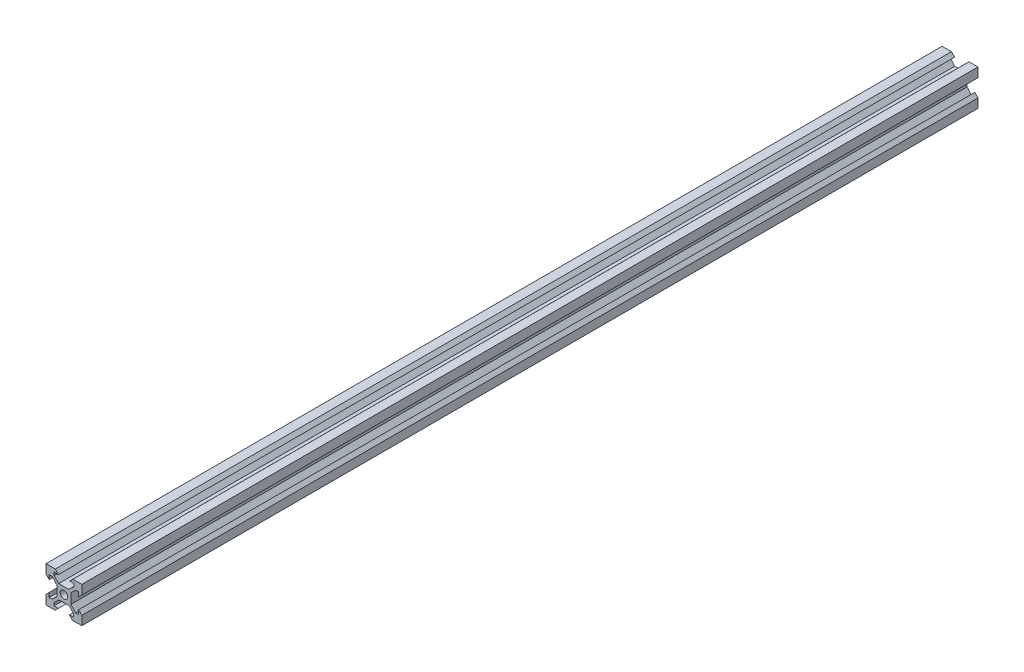
SolidWorks part; units mm, degrees
material "1060-H12"
ref_plane "Płaszczyzna przednia" through (0, 0, 0) normal (0, 0, 1) x (1, 0, 0)
ref_plane "Płaszczyzna górna" through (0, 0, 0) normal (0, 1, 0) x (1, 0, 0)
ref_plane "Płaszczyzna prawa" through (0, 0, 0) normal (1, 0, 0) x (0, 0, -1)
sketch "Szkic1" plane through (0, 0, 0) normal (0, 0, 1) x (1, 0, 0)
  line L0 (7.0398, 13.8855) -> (12.7198, 13.8855)
  line L1 (0, 0) -> (5, 0)
  line L2 (0, 0) -> (0, 5.1987)
  line L3 (0, 20) -> (5.1987, 20)
  line L4 (20, 0) -> (20, 5)
  line L6 (6.9691, 18.1996) -> (5.1987, 20)
  line L7 (13.1691, 18.1996) -> (15, 20)
  line L9 (15, 20) -> (20, 20)
  line L10 (4.5691, 18.1996) -> (6.9691, 18.1996)
  line L11 (4.5691, 18.1996) -> (4.5691, 16.5388)
  line L12 (15.5691, 18.1996) -> (15.5691, 16.5388)
  line L13 (0, 10) -> (20, 10) construction
  line L14 (4.5691, 16.5388) -> (7.0398, 13.8855)
  line L15 (12.7198, 13.8855) -> (15.5691, 16.5388)
  line L16 (13.1691, 18.1996) -> (15.5691, 18.1996)
  line L17 (18.1996, 13.0309) -> (20, 14.8013)
  line L18 (18.1996, 15.4309) -> (18.1996, 13.0309)
  line L19 (18.1996, 15.4309) -> (16.5388, 15.4309)
  line L20 (16.5388, 15.4309) -> (13.8855, 12.9602)
  line L21 (13.8855, 12.9602) -> (13.8855, 7.2802)
  line L22 (13.8855, 7.2802) -> (16.5388, 4.4309)
  line L23 (18.1996, 4.4309) -> (16.5388, 4.4309)
  line L24 (18.1996, 6.8309) -> (18.1996, 4.4309)
  line L25 (18.1996, 6.8309) -> (20, 5)
  line L26 (13.0309, 1.8004) -> (14.8013, 0)
  line L27 (15.4309, 1.8004) -> (13.0309, 1.8004)
  line L28 (15.4309, 1.8004) -> (15.4309, 3.4612)
  line L29 (15.4309, 3.4612) -> (12.9602, 6.1145)
  line L30 (12.9602, 6.1145) -> (7.2802, 6.1145)
  line L31 (7.2802, 6.1145) -> (4.4309, 3.4612)
  line L32 (4.4309, 1.8004) -> (4.4309, 3.4612)
  line L33 (6.8309, 1.8004) -> (4.4309, 1.8004)
  line L34 (6.8309, 1.8004) -> (5, 0)
  line L35 (1.8004, 6.9691) -> (0, 5.1987)
  line L36 (1.8004, 4.5691) -> (1.8004, 6.9691)
  line L37 (1.8004, 4.5691) -> (3.4612, 4.5691)
  line L38 (3.4612, 4.5691) -> (6.1145, 7.0398)
  line L39 (6.1145, 7.0398) -> (6.1145, 12.7198)
  line L40 (6.1145, 12.7198) -> (3.4612, 15.5691)
  line L41 (1.8004, 15.5691) -> (3.4612, 15.5691)
  line L42 (1.8004, 13.1691) -> (1.8004, 15.5691)
  line L43 (1.8004, 13.1691) -> (0, 15)
  line L44 (0, 15) -> (0, 20)
  line L45 (14.8013, 0) -> (20, 0)
  line L46 (20, 14.8013) -> (20, 20)
  circle A0 centre (10, 10) radius 2.1
  dimension "D3" = 6.2
  dimension "D1" = 20
  dimension "D2" = 20
  dimension "D4" = 2.4
  dimension "D5" = 2.4
  dimension "D6" = 360
  dimension "D7" = 1.4716
  dimension "D8" = 90
  dimension "D9" = 5.68
  dimension "D19" = 4
extrude "Dodanie-wyciągnięcie1" add sketch "Szkic1" along normal blind 500
